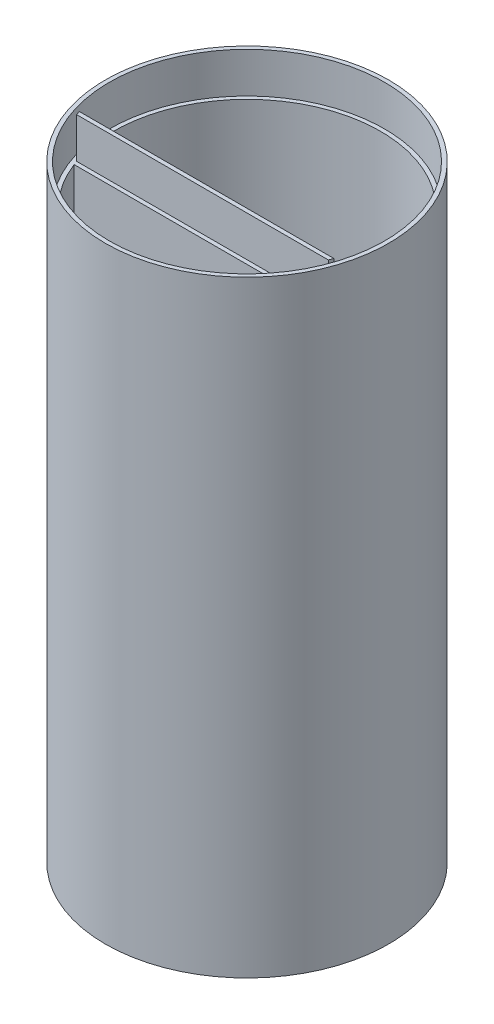
SolidWorks part; units mm, degrees
ref_plane "Front Plane" through (0, 0, 0) normal (0, 0, 1) x (1, 0, 0)
ref_plane "Top Plane" through (0, 0, 0) normal (0, 1, 0) x (1, 0, 0)
ref_plane "Right Plane" through (0, 0, 0) normal (1, 0, 0) x (0, 0, -1)
sketch "Sketch1" plane through (0, 0, 0) normal (0, 1, 0) x (1, 0, 0)
  line L0 (-31.4484, -10) -> (31.4484, -10)
  line L1 (-30.7409, -12) -> (30.7409, -12)
  arc A0 (31.4484, -10) -> (-31.4484, -10) centre (0, 0) ccw
  circle A1 centre (0, 0) radius 35
  arc A2 (30.7409, -12) -> (31.4484, -10) centre (0, 0) ccw construction
  circle A3 centre (0, 0) radius 33 construction
  arc A4 (-31.4484, -10) -> (-30.7409, -12) centre (0, 0) ccw construction
  arc A5 (-30.7409, -12) -> (30.7409, -12) centre (0, 0) ccw
  dimension "D2" = 70
  dimension "D3" = 2
  dimension "D4" = 10
  dimension "D1" = 2
extrude "Boss-Extrude1" add sketch "Sketch1" along normal blind 150
sketch "Sketch3" plane through (0, 150, 0) normal (0, 1, 0) x (1, 0, 0)
  line L0 (33, 0) -> (35, 0) construction
  line L1 (-31.4484, -10) -> (31.4484, -10) construction
  line L2 (-31.4484, -10) -> (31.4484, -10) construction
  line L3 (-31.1127, -11) -> (31.1127, -11)
  line L4 (0, -10) -> (0, -12) construction
  line L5 (30.7409, -12) -> (-30.7409, -12) construction
  line L6 (30.7409, -12) -> (-30.7409, -12)
  circle A0 centre (0, 0) radius 34
  arc A3 (31.4484, -10) -> (-31.4484, -10) centre (0, 0) ccw construction
  circle A4 centre (0, 0) radius 35 construction
  circle A5 centre (0, 0) radius 35
  arc A6 (-31.6679, -9.2813) -> (-31.1127, -11) centre (0, 0) ccw
  arc A11 (33, 0) -> (-31.6679, -9.2813) centre (0, 0) ccw
  arc A12 (-31.1127, -11) -> (31.1127, -11) centre (0, 0) ccw
  arc A13 (31.1127, -11) -> (33, 0) centre (0, 0) ccw
  point P3 (34, 0)
  point P21 (0, -11)
extrude "Cut-Extrude1" cut sketch "Sketch3" against normal blind 10
